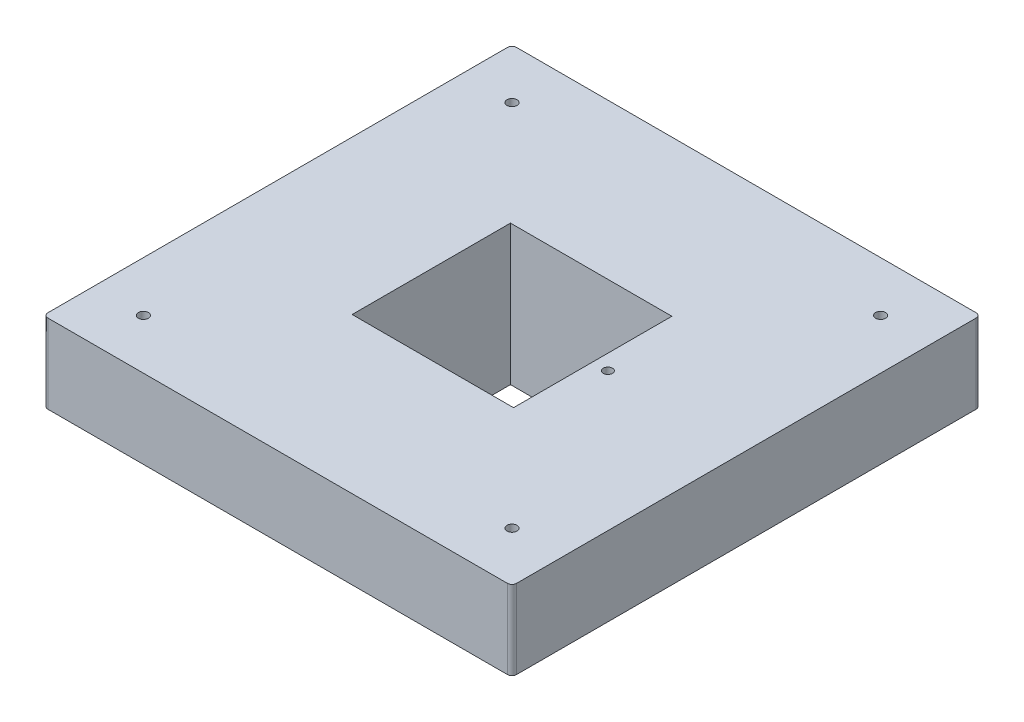
SolidWorks part; units mm, degrees
material "ABS"
ref_plane "Front Plane" through (0, 0, 0) normal (0, 0, 1) x (1, 0, 0)
ref_plane "Top Plane" through (0, 0, 0) normal (0, 1, 0) x (1, 0, 0)
ref_plane "Right Plane" through (0, 0, 0) normal (1, 0, 0) x (0, 0, -1)
sketch "Sketch1" plane through (0, 0, 0) normal (0, 1, 0) x (1, 0, 0)
  line L1 (-26.5, 26) -> (26.5, 26)
  line L2 (-26.5, 26) -> (-26.5, -26)
  line L3 (-26.5, -26) -> (26.5, -26)
  line L4 (26.5, 26) -> (26.5, -26)
  line L5 (-60.5282, 60.5282) -> (60.5282, 60.5282) construction
  line L6 (-60.5282, 60.5282) -> (-60.5282, -60.5282) construction
  line L7 (-60.5282, -60.5282) -> (60.5282, -60.5282) construction
  line L8 (60.5282, 60.5282) -> (60.5282, -60.5282) construction
  line L9 (-76.96, -76.96) -> (76.96, -76.96)
  line L10 (-76.96, -76.96) -> (-76.96, 76.96)
  line L11 (-76.96, 76.96) -> (76.96, 76.96)
  line L12 (76.96, -76.96) -> (76.96, 76.96)
  line L14 (0, 0) -> (0, -26) construction
  circle A0 centre (0, 0) radius 55 construction
  circle A1 centre (-60.5282, 60.5282) radius 2 construction
  circle A2 centre (60.5282, 60.5282) radius 2 construction
  circle A3 centre (60.5282, -60.5282) radius 2 construction
  circle A4 centre (-60.5282, -60.5282) radius 2 construction
  circle A5 centre (31.5, 0) radius 1.5
  point P4 (0, 26)
  point P6 (-26.5, 0)
  point P11 (0, 60.5282)
  point P12 (-60.5282, 0)
  point P24 (0, 76.96)
  point P25 (-76.96, 0)
  dimension "D3" = 110
  dimension "D6" = 4
  dimension "D7" = 3
  dimension "D1" = 53
  dimension "D2" = 52
  dimension "D4" = 121.0564
  dimension "D5" = 153.92
  dimension "D8" = 5
extrude "Boss-Extrude1" add sketch "Sketch1" against normal blind 25.95
sketch "Sketch3" plane through (0, -25.95, 0) normal (0, -1, 0) x (1, 0, 0)
  line L1 (-26.5, 26) -> (26.5, 26)
  line L2 (-26.5, 26) -> (-26.5, -26)
  line L3 (-26.5, -26) -> (26.5, -26)
  line L4 (26.5, 26) -> (26.5, -26)
  circle A0 centre (0, 0) radius 55
  circle A1 centre (0, 0) radius 55 construction
hole_wizard "Tap Drill for M4x0.7 Tap2" positions "3DSketch2" profile "Sketch4" hole size "M4x0.7" standard "ANSI Metric" end condition through all
sketch3d "3DSketch2"
  point P0 (-60.5282, 0, -60.5282)
  point P2 (-60.5282, 0, 60.5282)
  point P4 (60.5282, 0, 60.5282)
  point P6 (60.5282, 0, -60.5282)
sketch "Sketch4" plane through (-60.5282, 0, -60.5282) normal (1, 0, 0) x (0, 0, 1)
  line L0 (0, 0) -> (0, 25.95)
  line L1 (0, 25.95) -> (1.65, 25.95)
  line L2 (1.65, 25.95) -> (1.65, 0)
  line L5 (1.65, 0) -> (0, 0)
  line L11 (0, -6.35) -> (0, 107.95) construction
  dimension "Thru Hole Dia." = 3.3
  dimension "Thru Hole Depth" = 25.95
extrude "Boss-Extrude3" add sketch "Sketch3" along normal blind 20 contours A0
sketch "Sketch5" plane through (0, -45.95, 0) normal (0, -1, 0) x (1, 0, 0)
  line L0 (-37.5, 0) -> (37.5, 0) construction
  circle A0 centre (-37.5, 0) radius 3.225
  circle A1 centre (37.5, 0) radius 3.225
  point P4 (0, 0)
  dimension "D2" = 6.45
  dimension "D1" = 75
extrude "Cut-Extrude1" cut sketch "Sketch5" against normal blind 6.35
fillet "Fillet2" radius 1.5 4 edges at (-76.96, -12.975, -76.96) (76.96, -12.975, -76.96) (-76.96, -12.975, 76.96) (76.96, -12.975, 76.96)
